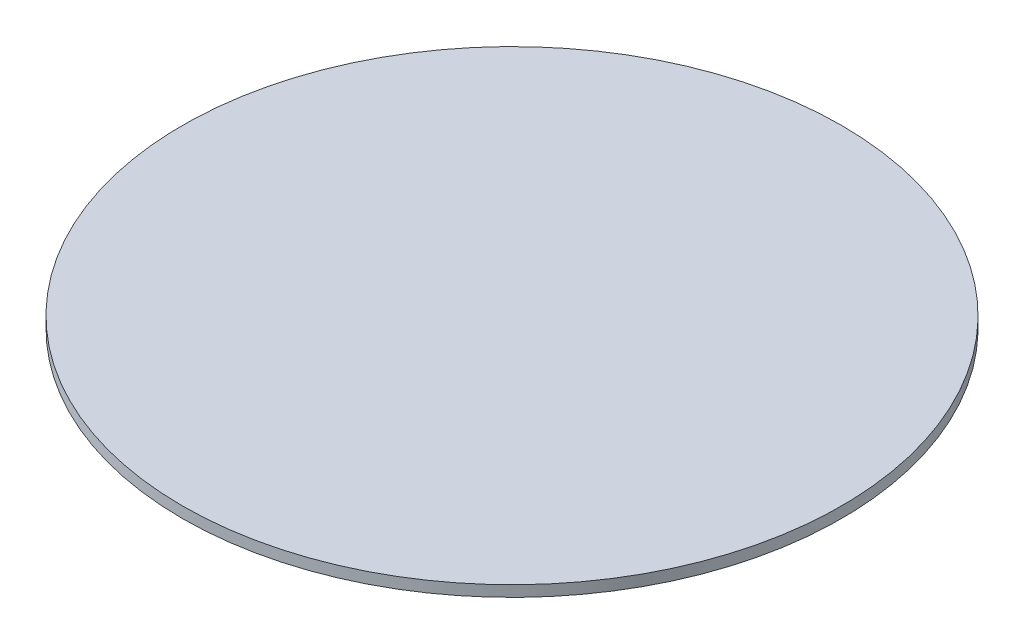
SolidWorks part; units mm, degrees
ref_plane "前视基准面" through (0, 0, 0) normal (0, 0, 1) x (1, 0, 0)
ref_plane "上视基准面" through (0, 0, 0) normal (0, 1, 0) x (1, 0, 0)
ref_plane "右视基准面" through (0, 0, 0) normal (1, 0, 0) x (0, 0, -1)
other "Configuration Table"
sketch "草图1" plane through (0, 0, 0) normal (0, 1, 0) x (1, 0, 0)
  circle A0 centre (0, 0) radius 60
  dimension "D1" = 120
extrude "凸台-拉伸1" add sketch "草图1" along normal blind 2
